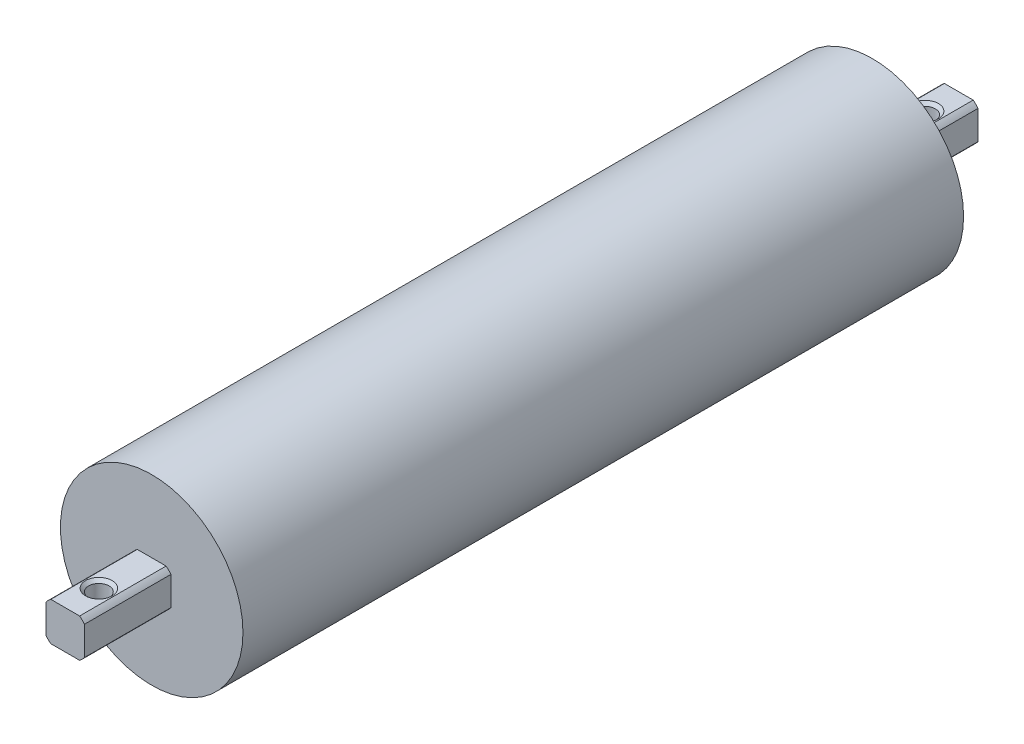
SolidWorks part; units mm, degrees
material "45"
ref_plane "前视基准面" through (0, 0, 0) normal (0, 0, 1) x (1, 0, 0)
ref_plane "上视基准面" through (0, 0, 0) normal (0, 1, 0) x (1, 0, 0)
ref_plane "右视基准面" through (0, 0, 0) normal (1, 0, 0) x (0, 0, -1)
other "Configuration Table"
sketch "草图1" plane through (0, 0, 0) normal (0, 0, 1) x (1, 0, 0)
  circle A0 centre (0, 0) radius 38
  dimension "D1" = 76
extrude "凸台-拉伸1" add sketch "草图1" along normal mid plane 300
sketch "草图2" plane through (0, 0, 150) normal (0, 0, 1) x (1, 0, 0)
  circle A0 centre (0, 0) radius 10
  dimension "D1" = 20
extrude "凸台-拉伸2" add sketch "草图2" along normal blind 36
ref_plane "基准面1" through (0, 0, 0) normal (0, 0, 1) x (1, 0, 0)
sketch "草图3" plane through (0, 0, 186) normal (0, 0, 1) x (1, 0, 0)
  line L1 (-8, 8) -> (8, 8)
  line L2 (-8, 8) -> (-8, -8)
  line L3 (-8, -8) -> (8, -8)
  line L4 (8, 8) -> (8, -8)
  line L5 (-8, 8) -> (8, -8) construction
  line L6 (-8, -8) -> (8, 8) construction
  point P0 (0, 0)
  dimension "D1" = 16
extrude "切除-拉伸1" cut sketch "草图3" against normal blind 36 flip side to cut
hole_wizard "M10 螺纹孔1" positions "草图4" profile "草图5" tap size "M10" standard "GB"
sketch "草图4" plane through (0, 8, 0) normal (0, 1, 0) x (1, 0, 0)
  line L0 (6, -186) -> (-6, -186) construction
  line L1 (-8, -186) -> (-8, -150) construction
  point P0 (0, -172)
  dimension "D1" = 14
  dimension "D2" = 8
sketch "草图5" plane through (0, 8, 172) normal (1, 0, 0) x (0, 0, 1)
  line L0 (0, 0) -> (0, 27.0537)
  line L1 (0, 27.0537) -> (4.25, 24.5)
  line L2 (4.25, 24.5) -> (4.25, 1.275)
  line L3 (4.25, 1.275) -> (5.525, 0)
  line L5 (5.525, 0) -> (0, 0)
  line L6 (-4.25, 1.275) -> (-5.525, 0) construction
  line L10 (0, 27.0537) -> (-4.25, 24.5) construction
  line L11 (0, -6.35) -> (0, 107.95) construction
  dimension "螺纹孔钻头直径" = 8.5
  dimension "螺纹孔钻头深度" = 24.5
  dimension "近端锥形沉头孔直径" = 11.05
  dimension "近端锥形沉头孔角度" = 90
  dimension "导头角度" = 118
cosmetic thread "孔螺纹线1"
mirror "镜向1" about plane through (0, 0, 0) normal (0, 0, 1) of "M10 螺纹孔1", "凸台-拉伸2", "切除-拉伸1"
